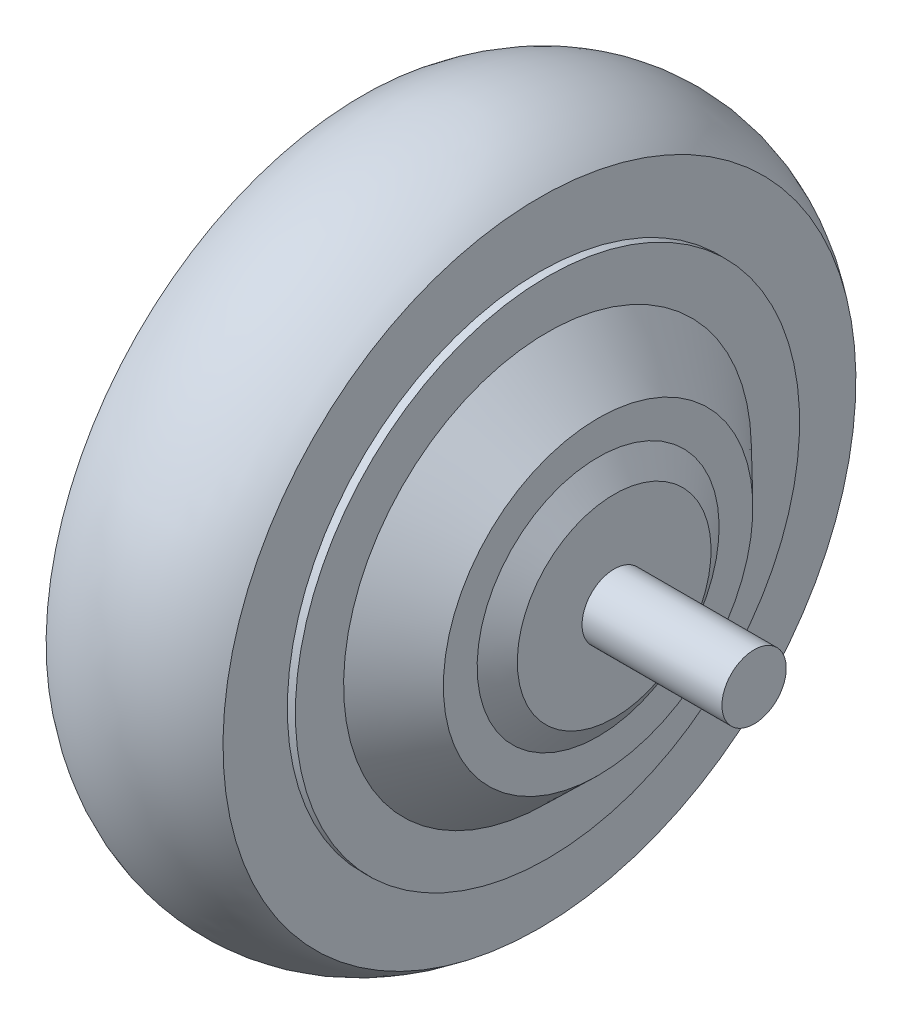
SolidWorks part; units mm, degrees
ref_plane "Alzado" through (0, 0, 0) normal (0, 0, 1) x (1, 0, 0)
ref_plane "Planta" through (0, 0, 0) normal (0, 1, 0) x (1, 0, 0)
ref_plane "Vista lateral" through (0, 0, 0) normal (1, 0, 0) x (0, 0, -1)
sketch "Croquis1" plane through (0, 0, 0) normal (0, 0, 1) x (1, 0, 0)
  line L0 (-68.5997, 0) -> (88.5126, 0) construction
  line L1 (0, 0) -> (0, 194.2371) construction
  line L2 (-22, 165.2213) -> (-22, 149.2213)
  line L3 (-36.0173, 173) -> (88.5126, 173) construction
  line L4 (22, 165.2213) -> (22, 149.2213)
  line L5 (-36.0173, 0) -> (88.5126, 0) construction
  line L6 (-24, 149.2213) -> (-24, 137.2213)
  line L7 (24, 149.2213) -> (24, 137.2213)
  line L8 (-24, 149.2213) -> (-22, 149.2213)
  line L9 (24, 149.2213) -> (22, 149.2213)
  line L10 (-24, 137.2213) -> (-34.6, 125)
  line L11 (-34.6, 125) -> (-34.6, 86.5)
  line L12 (24, 137.2213) -> (36.6, 125)
  line L13 (36.6, 125) -> (36.6, 116.6)
  line L15 (36.6, 116.6) -> (40.6, 110.6)
  line L16 (40.6, 110.6) -> (40.6, 94.5)
  line L17 (75.4, 94.5) -> (40.6, 94.5)
  line L18 (75.4, 94.5) -> (75.4, 86.5)
  line L19 (-34.6, 86.5) -> (75.4, 86.5)
  line L20 (-68.5997, 86.5) -> (88.5126, 86.5) construction
  arc A1 (22, 165.2213) -> (-22, 165.2213) centre (0, 138) ccw
  dimension "D4" = 35
  dimension "D5" = 2
  dimension "D1" = 173
  dimension "D2" = 44
  dimension "D3" = 22
  dimension "D6" = 2
  dimension "D7" = 16
  dimension "D8" = 16
  dimension "D9" = 10.6
  dimension "D10" = 12.6
  dimension "D11" = 12
  dimension "D12" = 12
  dimension "D13" = 38.5
  dimension "D14" = 8
  dimension "D15" = 4
  dimension "D16" = 6
  dimension "D17" = 110
  dimension "D18" = 12.2213
  dimension "D19" = 12.2213
  dimension "D20" = 86.5
  dimension "D21" = 8.4
revolve "Revolución1" add sketch "Croquis1" angle 360 about L19
